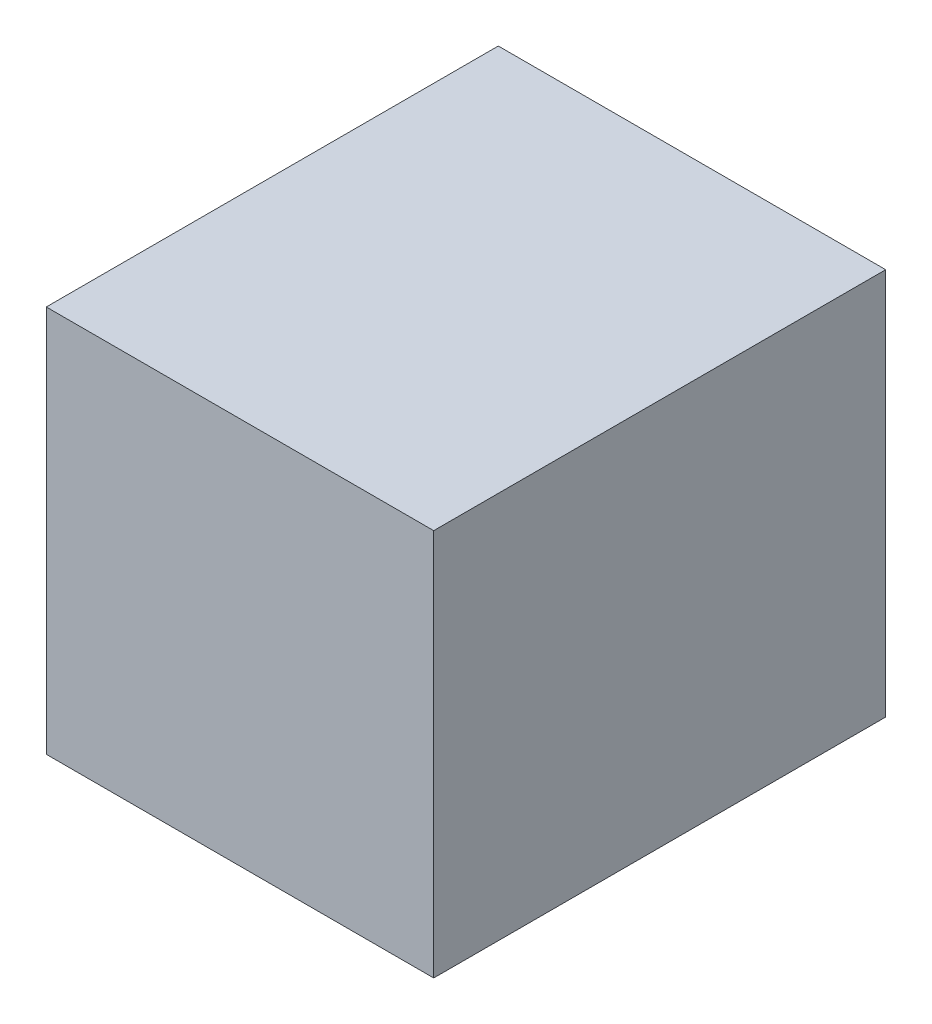
SolidWorks part; units mm, degrees
ref_plane "Front Plane" through (0, 0, 0) normal (0, 0, 1) x (1, 0, 0)
ref_plane "Top Plane" through (0, 0, 0) normal (0, 1, 0) x (1, 0, 0)
ref_plane "Right Plane" through (0, 0, 0) normal (1, 0, 0) x (0, 0, -1)
sketch "Sketch1" plane through (0, 0, 0) normal (0, 1, 0) x (1, 0, 0)
  line L1 (-300, 350) -> (300, 350)
  line L2 (-300, 350) -> (-300, -350)
  line L3 (-300, -350) -> (300, -350)
  line L4 (300, 350) -> (300, -350)
  line L5 (-300, 350) -> (300, -350) construction
  line L6 (-300, -350) -> (300, 350) construction
  point P0 (0, 0)
  dimension "D1" = 600
  dimension "D2" = 700
extrude "Boss-Extrude1" add sketch "Sketch1" along normal blind 600
